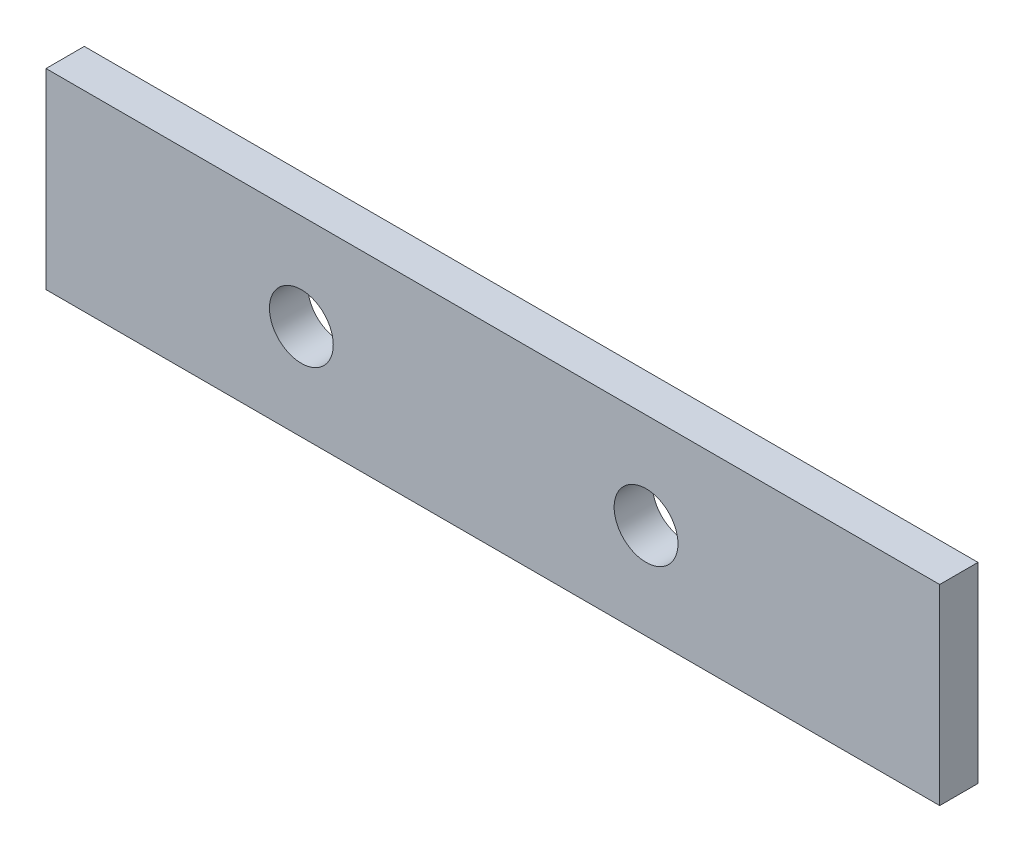
SolidWorks part; units mm, degrees
ref_plane "Front Plane" through (0, 0, 0) normal (0, 0, 1) x (1, 0, 0)
ref_plane "Top Plane" through (0, 0, 0) normal (0, 1, 0) x (1, 0, 0)
ref_plane "Right Plane" through (0, 0, 0) normal (1, 0, 0) x (0, 0, -1)
sketch "Sketch1" plane through (0, 0, 0) normal (0, 0, 1) x (1, 0, 0)
  line L1 (-350, 75) -> (350, 75)
  line L2 (-350, 75) -> (-350, -75)
  line L3 (-350, -75) -> (350, -75)
  line L4 (350, 75) -> (350, -75)
  line L5 (-350, 75) -> (350, -75) construction
  line L6 (-350, -75) -> (350, 75) construction
  circle A0 centre (-150, 0) radius 25
  circle A1 centre (120, 0) radius 25
  point P0 (0, 0)
  point P10 (0, 0)
  dimension "D4" = 50
  dimension "D1" = 230
  dimension "D2" = 75
  dimension "D3" = 150
  dimension "D5" = 700
  dimension "D6" = 270
extrude "Boss-Extrude1" add sketch "Sketch1" against normal blind 30
